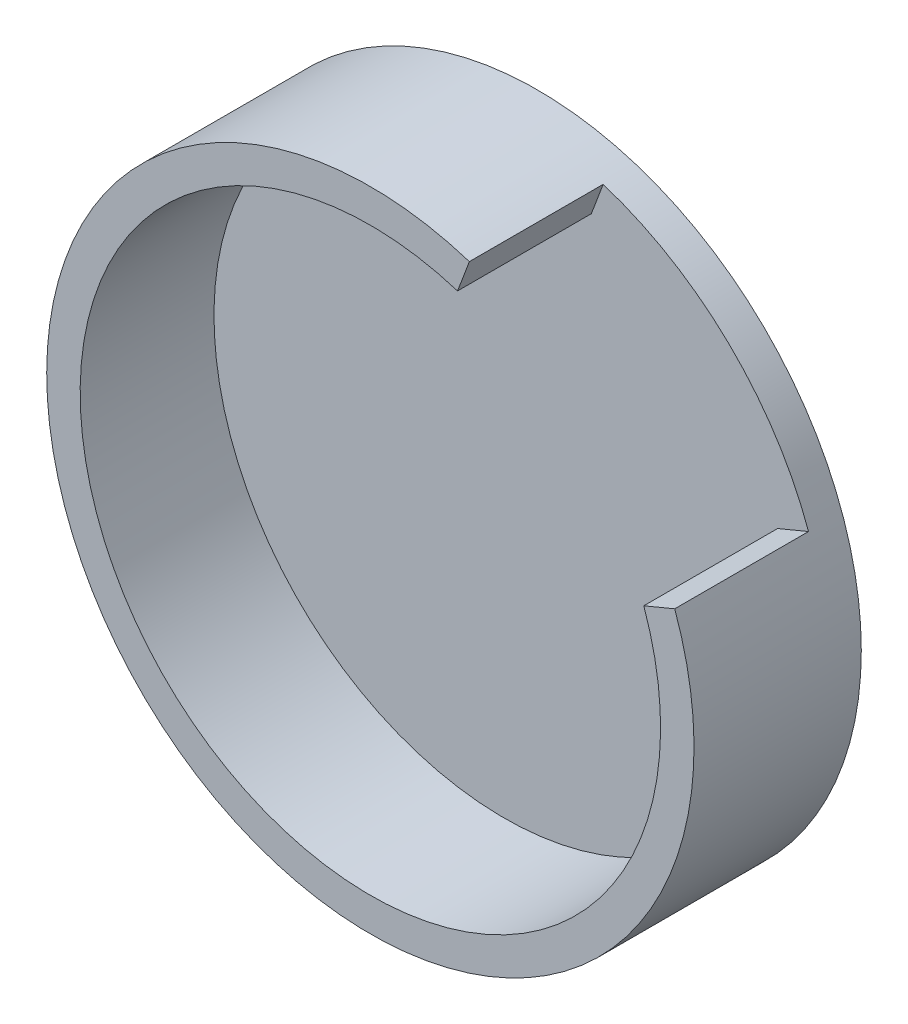
SolidWorks part; units mm, degrees
ref_plane "Alzado" through (0, 0, 0) normal (0, 0, 1) x (1, 0, 0)
ref_plane "Planta" through (0, 0, 0) normal (0, 1, 0) x (1, 0, 0)
ref_plane "Vista lateral" through (0, 0, 0) normal (1, 0, 0) x (0, 0, -1)
sketch "Croquis1" plane through (0, 0, 0) normal (0, 0, 1) x (1, 0, 0)
  circle A0 centre (0, 0) radius 19.35
  dimension "D1" = 38.7
extrude "Saliente-Extruir1" add sketch "Croquis1" along normal blind 10
shell "Vaciado1" thickness 2
sketch "Croquis2" plane through (0, 0, 10) normal (0, 0, 1) x (1, 0, 0)
  line L6 (5.9187, 18.4226) -> (5.2121, 16.5486)
  line L11 (16.3463, 5.8155) -> (18.1953, 6.5845)
  circle A1 centre (0, 0) radius 19.35 construction
  circle A2 centre (0, 0) radius 17.35 construction
  arc A3 (5.9187, 18.4226) -> (18.1953, 6.5845) centre (3.491, 3.6203) cw
  arc A4 (16.3463, 5.8155) -> (5.2121, 16.5486) centre (-1.2657, -1.313) ccw
  dimension "D1" = 15
  dimension "D2" = 19
extrude "Cortar-Extruir1" cut sketch "Croquis2" against normal blind 8
